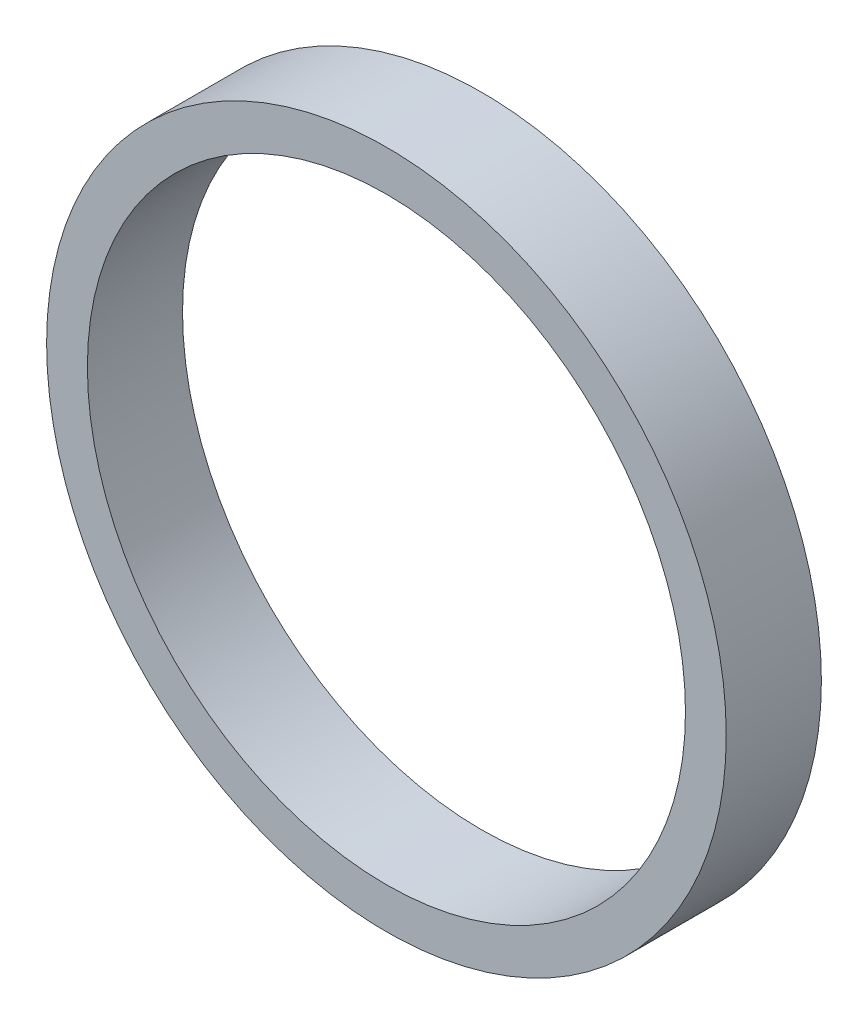
SolidWorks part; units mm, degrees
ref_plane "Front Plane" through (0, 0, 0) normal (0, 0, 1) x (1, 0, 0)
ref_plane "Top Plane" through (0, 0, 0) normal (0, 1, 0) x (1, 0, 0)
ref_plane "Right Plane" through (0, 0, 0) normal (1, 0, 0) x (0, 0, -1)
sketch "Sketch1" plane through (0, 0, 0) normal (0, 0, 1) x (1, 0, 0)
  circle A0 centre (0, 0) radius 12.5
  dimension "D1" = 25
extrude "Boss-Extrude1" add sketch "Sketch1" along normal blind 3.5
sketch "Sketch2" plane through (0, 0, 3.5) normal (0, 0, 1) x (1, 0, 0)
  circle A0 centre (0, 0) radius 11
  dimension "D1" = 22
extrude "Cut-Extrude1" cut sketch "Sketch2" against normal blind 3.5 contours A0
